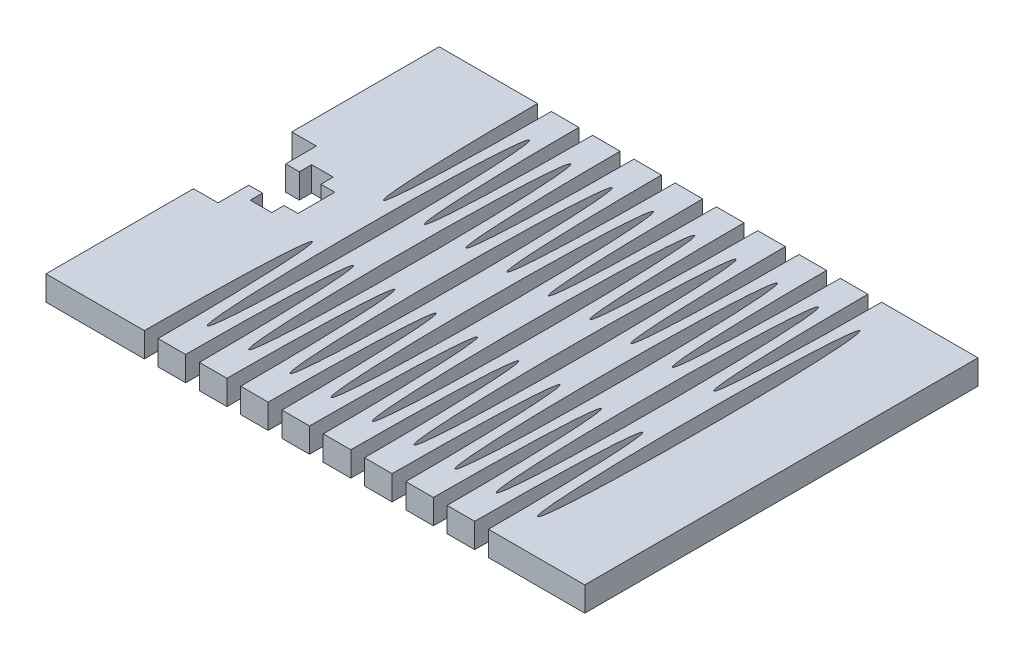
SolidWorks part; units mm, degrees
ref_plane "Front Plane" through (0, 0, 0) normal (0, 0, 1) x (1, 0, 0)
ref_plane "Top Plane" through (0, 0, 0) normal (0, 1, 0) x (1, 0, 0)
ref_plane "Right Plane" through (0, 0, 0) normal (1, 0, 0) x (0, 0, -1)
sketch "Sketch1" plane through (0, 0, 0) normal (0, 1, 0) x (1, 0, 0)
  line L0 (0, 19.05) -> (3.175, 19.05)
  line L1 (0, 0) -> (12.7, 0)
  line L2 (0, 0) -> (0, 19.05)
  line L3 (0, 50.8) -> (12.7, 50.8)
  line L4 (16.256, 46.1962) -> (16.256, 50.8) construction
  line L5 (3.175, 19.05) -> (3.175, 23.0187)
  line L6 (3.175, 31.75) -> (0, 31.75)
  line L7 (3.175, 23.0187) -> (4.953, 23.0187)
  line L8 (4.953, 23.0187) -> (4.953, 21.4312)
  line L9 (4.953, 21.4312) -> (7.7311, 21.4312)
  line L10 (7.7311, 21.4312) -> (7.7311, 23.0187)
  line L11 (7.7311, 23.0187) -> (9.525, 23.0187)
  line L12 (9.525, 23.0187) -> (9.525, 27.7813)
  line L13 (9.525, 27.7813) -> (7.7311, 27.7813)
  line L14 (7.7311, 27.7813) -> (7.7311, 29.3688)
  line L15 (7.7311, 29.3688) -> (4.953, 29.3688)
  line L16 (4.953, 29.3688) -> (4.953, 27.7813)
  line L17 (4.953, 27.7813) -> (3.175, 27.7813)
  line L18 (3.175, 27.7813) -> (3.175, 31.75)
  line L19 (0, 31.75) -> (0, 50.8)
  line L23 (14.478, 50.8) -> (18.034, 50.8)
  line L24 (19.812, 50.8) -> (23.368, 50.8)
  line L25 (23.368, 0) -> (19.812, 0)
  line L26 (25.146, 50.8) -> (28.702, 50.8)
  line L27 (18.034, 0) -> (14.478, 0)
  line L28 (28.702, 0) -> (25.146, 0)
  line L29 (30.48, 50.8) -> (34.036, 50.8)
  line L30 (12.7, 50.8) -> (13.589, 50.8) construction
  line L31 (13.589, 50.8) -> (14.478, 50.8) construction
  line L32 (12.7, 0) -> (13.589, 0) construction
  line L33 (13.589, 0) -> (14.478, 0) construction
  line L34 (34.036, 0) -> (30.48, 0)
  line L35 (35.814, 50.8) -> (39.37, 50.8)
  line L36 (39.37, 0) -> (35.814, 0)
  line L37 (41.148, 50.8) -> (44.704, 50.8)
  line L38 (44.704, 0) -> (41.148, 0)
  line L39 (46.482, 50.8) -> (50.038, 50.8)
  line L40 (50.038, 0) -> (46.482, 0)
  line L41 (51.816, 50.8) -> (55.372, 50.8)
  line L42 (55.372, 0) -> (51.816, 0)
  line L43 (57.15, 50.8) -> (60.706, 50.8)
  line L44 (60.706, 0) -> (57.15, 0)
  line L45 (60.706, 50.8) -> (69.596, 50.8)
  line L46 (69.596, 50.8) -> (69.596, 0)
  line L47 (69.596, 0) -> (60.706, 0)
  ellipse E0 centre (16.256, 25.4) end of major axis (16.256, 4.6037) minor radius 0.9525
  ellipse E1 centre (13.589, 50.8) end of major axis (13.589, 71.5962) minor radius 0.889 (14.478, 50.8) -> (12.7, 50.8) cw
  ellipse E2 centre (13.589, 0) end of major axis (13.589, 20.7962) minor radius 0.889 (14.478, 0) -> (12.7, 0) ccw
  ellipse E3 centre (18.923, 50.8) end of major axis (18.923, 71.5962) minor radius 0.889 (19.812, 50.8) -> (18.034, 50.8) cw
  ellipse E4 centre (21.59, 25.4) end of major axis (21.59, 4.6037) minor radius 0.9525
  ellipse E5 centre (18.923, 0) end of major axis (18.923, 20.7962) minor radius 0.889 (19.812, 0) -> (18.034, 0) ccw
  ellipse E6 centre (24.257, 50.8) end of major axis (24.257, 30.0038) minor radius 0.889 (25.146, 50.8) -> (23.368, 50.8) cw
  ellipse E7 centre (26.924, 25.4) end of major axis (26.924, 4.6037) minor radius 0.9525
  ellipse E8 centre (24.257, 0) end of major axis (24.257, 20.7962) minor radius 0.889 (25.146, 0) -> (23.368, 0) ccw
  ellipse E9 centre (29.591, 50.8) end of major axis (29.591, 30.0038) minor radius 0.889 (30.48, 50.8) -> (28.702, 50.8) cw
  ellipse E10 centre (32.258, 25.4) end of major axis (32.258, 4.6037) minor radius 0.9525
  ellipse E11 centre (29.591, 0) end of major axis (29.591, 20.7962) minor radius 0.889 (30.48, 0) -> (28.702, 0) ccw
  ellipse E12 centre (34.925, 50.8) end of major axis (34.925, 30.0038) minor radius 0.889 (35.814, 50.8) -> (34.036, 50.8) cw
  ellipse E13 centre (37.592, 25.4) end of major axis (37.592, 4.6037) minor radius 0.9525
  ellipse E14 centre (34.925, 0) end of major axis (34.925, 20.7962) minor radius 0.889 (35.814, 0) -> (34.036, 0) ccw
  ellipse E15 centre (40.259, 50.8) end of major axis (40.259, 30.0038) minor radius 0.889 (41.148, 50.8) -> (39.37, 50.8) cw
  ellipse E16 centre (42.926, 25.4) end of major axis (42.926, 4.6037) minor radius 0.9525
  ellipse E17 centre (40.259, 0) end of major axis (40.259, 20.7962) minor radius 0.889 (41.148, 0) -> (39.37, 0) ccw
  ellipse E18 centre (45.593, 50.8) end of major axis (45.593, 30.0038) minor radius 0.889 (46.482, 50.8) -> (44.704, 50.8) cw
  ellipse E19 centre (48.26, 25.4) end of major axis (48.26, 4.6037) minor radius 0.9525
  ellipse E20 centre (45.593, 0) end of major axis (45.593, 20.7962) minor radius 0.889 (46.482, 0) -> (44.704, 0) ccw
  ellipse E21 centre (50.927, 50.8) end of major axis (50.927, 71.5962) minor radius 0.889 (51.816, 50.8) -> (50.038, 50.8) cw
  ellipse E22 centre (53.594, 25.4) end of major axis (53.594, 4.6037) minor radius 0.9525
  ellipse E23 centre (50.927, 0) end of major axis (50.927, 20.7962) minor radius 0.889 (51.816, 0) -> (50.038, 0) ccw
  ellipse E24 centre (56.261, 50.8) end of major axis (56.261, 71.5962) minor radius 0.889 (57.15, 50.8) -> (55.372, 50.8) cw
  ellipse E25 centre (58.928, 25.4) end of major axis (58.928, 4.6037) minor radius 0.9525
  ellipse E26 centre (56.261, 0) end of major axis (56.261, 20.7962) minor radius 0.889 (57.15, 0) -> (55.372, 0) ccw
  dimension "D2" = 4.7625
  dimension "D3" = 12.7
  dimension "D4" = 7.9375
  dimension "D6" = 9.525
  dimension "D7" = 50.8
  dimension "D8" = 12.7
  dimension "D9" = 3.175
  dimension "D10" = 2.7781
  dimension "D11" = 1.778
  dimension "D12" = 1.778
  dimension "D13" = 3.556
  dimension "D14" = 1.778
  dimension "D15" = 25.4
  dimension "D16" = 9
  dimension "D17" = 8.89
extrude "Boss-Extrude1" add sketch "Sketch1" along normal blind 3.175
equation "\"Plywood Thickness\"= 0.125"
equation "\"D9@Sketch1\"=\"Plywood Thickness\""
equation "\"D1@Boss-Extrude1\"=\"Plywood Thickness\""
